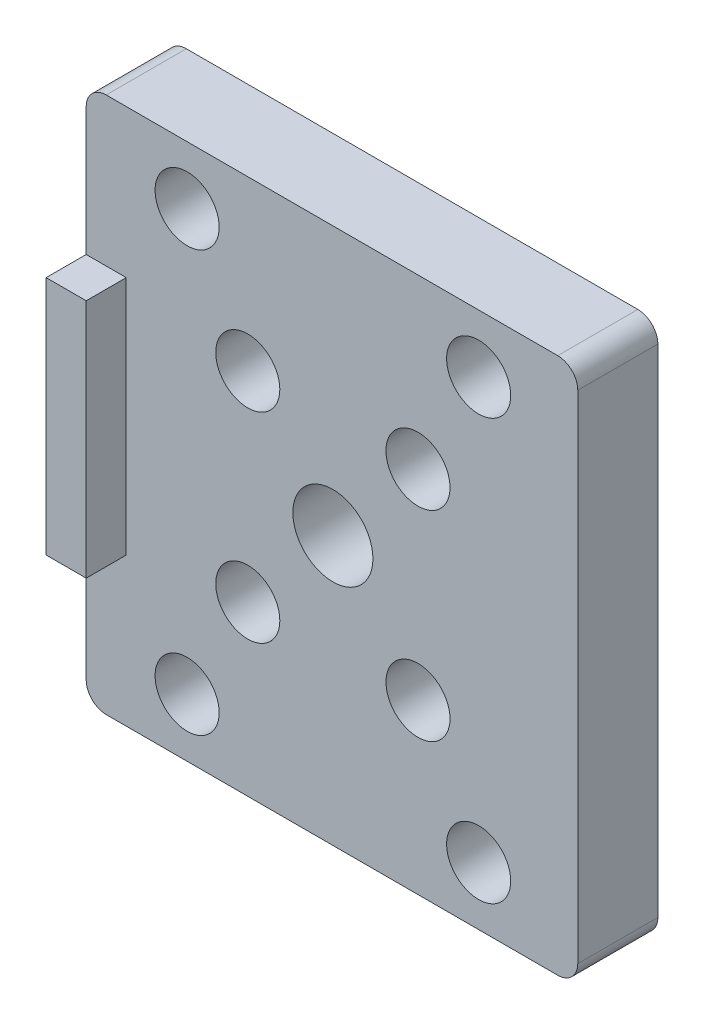
SolidWorks part; units mm, degrees
ref_plane "Piano frontale" through (0, 0, 0) normal (0, 0, 1) x (1, 0, 0)
ref_plane "Piano superiore" through (0, 0, 0) normal (0, 1, 0) x (1, 0, 0)
ref_plane "Piano destro" through (0, 0, 0) normal (1, 0, 0) x (0, 0, -1)
sketch "Schizzo1" plane through (0, 0, 0) normal (0, 0, 1) x (1, 0, 0)
  line L1 (-12.275, -13.4) -> (12.275, -13.4)
  line L2 (-12.275, -13.4) -> (-12.275, 13.4)
  line L3 (-12.275, 13.4) -> (12.275, 13.4)
  line L4 (12.275, -13.4) -> (12.275, 13.4)
  line L5 (-12.275, -13.4) -> (12.275, 13.4) construction
  line L6 (-12.275, 13.4) -> (12.275, -13.4) construction
  point P0 (0, 0)
  dimension "D1" = 24.55
  dimension "D2" = 26.8
extrude "Estrusione-Estrusione1" add sketch "Schizzo1" along normal blind 4
hole_wizard "Foro per Vite M3-1" positions "Schizzo2" profile "Schizzo3" hole size "M3" standard "ISO" end condition through all
sketch "Schizzo2" plane through (0, 0, 4) normal (0, 0, 1) x (1, 0, 0)
  line L0 (-12.275, 0) -> (12.275, 0) construction
  line L1 (-12.275, 13.4) -> (-12.275, -13.4) construction
  line L2 (12.275, -13.4) -> (12.275, 13.4) construction
  line L3 (12.275, -13.4) -> (12.275, 13.4) construction
  point P0 (-4.205, 5)
  point P2 (4.295, 5)
  point P4 (4.295, -5)
  point P6 (-4.205, -5)
  dimension "D1" = 8.5
  dimension "D2" = 10
  dimension "D3" = 5
  dimension "D4" = 7.98
sketch "Schizzo3" plane through (-4.205, 5, 4) normal (1, 0, 0) x (0, -1, 0)
  line L0 (0, 0) -> (0, 4)
  line L1 (0, 4) -> (1.6, 4)
  line L2 (1.6, 4) -> (1.6, 0)
  line L5 (1.6, 0) -> (0, 0)
  line L11 (0, -6.35) -> (0, 107.95) construction
  dimension "Thru Hole Dia." = 3.2
  dimension "Thru Hole Depth" = 4
hole_wizard "Foro per Vite M3-2" positions "Schizzo3D1" profile "Schizzo4" hole size "M3" standard "ISO" end condition through all
sketch3d "Schizzo3D1"
  line L2 (-12.275, 0, 4) -> (12.275, 0, 4) construction
  line L3 (-12.275, 13.4, 4) -> (-12.275, -13.4, 4) construction
  line L4 (12.275, -13.4, 4) -> (12.275, 13.4, 4) construction
  line L7 (0, -13.4, 4) -> (0, 13.4, 4) construction
  line L8 (-12.275, -13.4, 4) -> (12.275, -13.4, 4) construction
  line L9 (12.275, 13.4, 4) -> (-12.275, 13.4, 4) construction
  point P0 (-7.235, 10.5, 4)
  point P2 (7.325, 10.5, 4)
  point P4 (-7.235, -10.5, 4)
  point P6 (7.325, -10.5, 4)
  dimension "D3" = 10.5
  dimension "D1" = 21
  dimension "D2" = 14.56
  dimension "D4" = 4.95
sketch "Schizzo4" plane through (-7.235, 10.5, 4) normal (1, 0, 0) x (0, -1, 0)
  line L0 (0, 0) -> (0, 4)
  line L1 (0, 4) -> (1.6, 4)
  line L2 (1.6, 4) -> (1.6, 0)
  line L5 (1.6, 0) -> (0, 0)
  line L11 (0, -6.35) -> (0, 107.95) construction
  dimension "Thru Hole Dia." = 3.2
  dimension "Thru Hole Depth" = 4
sketch "Schizzo5" plane through (0, 0, 4) normal (0, 0, 1) x (1, 0, 0)
  line L0 (-12.275, 0) -> (12.275, 0) construction
  line L1 (-12.275, 13.4) -> (-12.275, -13.4) construction
  line L2 (12.275, -13.4) -> (12.275, 13.4) construction
  line L3 (12.275, -13.4) -> (12.275, 13.4) construction
  circle A0 centre (0.045, 0) radius 2
  dimension "D1" = 4
  dimension "D2" = 12.23
extrude "Taglio-Estrusione1" cut sketch "Schizzo5" against normal blind 10
sketch "Schizzo6" plane through (0, 0, 4) normal (0, 0, 1) x (1, 0, 0)
  line L0 (-12.275, 13.4) -> (-12.275, -13.4) construction
  line L1 (-12.275, -6) -> (-10.275, -6)
  line L2 (-12.275, -6) -> (-12.275, 6)
  line L3 (-12.275, 6) -> (-10.275, 6)
  line L4 (-10.275, -6) -> (-10.275, 6)
  line L5 (0, 0) -> (-11.359, 0) construction
  dimension "D1" = 12
  dimension "D2" = 2
  dimension "D3" = 6
extrude "Estrusione-Estrusione2" add sketch "Schizzo6" along normal blind 2
fillet "Raccordo1" radius 1 4 edges at (-12.275, -13.4, 2) (12.275, -13.4, 2) (-12.275, 13.4, 2) (12.275, 13.4, 2)
equation "\"D3@Schizzo3D1\"=\"D1@Schizzo3D1\"/2"
